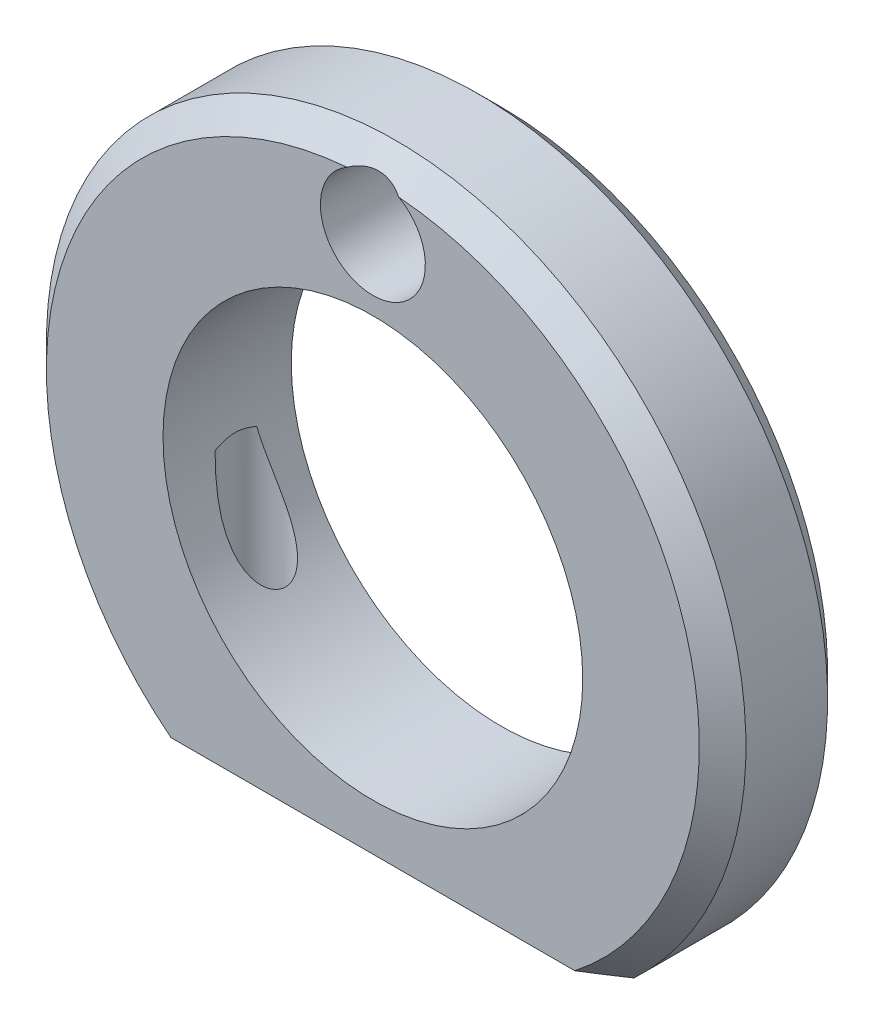
SolidWorks part; units mm, degrees
material "2A12"
ref_plane "前视基准面" through (0, 0, 0) normal (0, 0, 1) x (1, 0, 0)
ref_plane "上视基准面" through (0, 0, 0) normal (0, 1, 0) x (1, 0, 0)
ref_plane "右视基准面" through (0, 0, 0) normal (1, 0, 0) x (0, 0, -1)
sketch "草图1" plane through (0, 0, 0) normal (0, 0, 1) x (1, 0, 0)
  circle A0 centre (0, 0) radius 5.5
  circle A1 centre (0, 0) radius 7
  dimension "D1" = 11
  dimension "D2" = 14
extrude "拉伸1" add sketch "草图1" along normal mid plane 60
sketch "草图2" plane through (0, 0, 30) normal (0, 0, 1) x (1, 0, 0)
  line L0 (0, 0) -> (0, -11) construction
  line L1 (-10, 11) -> (10, 11) construction
  line L2 (-10, 11) -> (-10, -11) construction
  line L3 (-10, -11) -> (10, -11) construction
  line L4 (10, 11) -> (10, -11) construction
  circle A0 centre (0, 0) radius 5.5 construction
  circle A1 centre (0, 0) radius 5.5
  circle A2 centre (0, 0) radius 15
  dimension "D4" = 30
  dimension "D1" = 11
  dimension "D2" = 22
  dimension "D3" = 20
extrude "拉伸2" add sketch "草图2" against normal blind 7
mirror "镜向1" about plane through (0, 0, 0) normal (0, 0, 1) of "拉伸2"
sketch "草图4" plane through (0, 0, 30) normal (0, 0, 1) x (1, 0, 0)
  line L1 (-10.198, -11) -> (10.198, -11)
  line L2 (-10, -11) -> (10, -11) construction
  circle A0 centre (0, 0) radius 5.5 construction
  circle A1 centre (0, 0) radius 5.5
  circle A3 centre (0, 0) radius 15 construction
  arc A4 (10.198, -11) -> (-10.198, -11) centre (0, 0) ccw
extrude "拉伸3" [suppressed] add sketch "草图4" along normal blind 5
mirror "镜向2" [suppressed] about plane through (0, 0, 0) normal (0, 0, 1)
sketch "草图5" plane through (0, 0, 0) normal (1, 0, 0) x (0, 0, -1)
  line L0 (-30, 0) -> (30, 0) construction
  line L1 (-30, 15) -> (-30, -15) construction
  line L2 (30, -15) -> (30, 15) construction
  line L3 (-30, -11) -> (-24.5, -11)
  line L4 (-24.5, -11) -> (-24.5, -20)
  line L5 (24.5, -11) -> (24.5, -20)
  line L6 (-30, -11) -> (-30, -20)
  line L7 (-30, -20) -> (-24.5, -20)
  line L8 (30, -11) -> (30, -20)
  line L9 (30, -20) -> (24.5, -20)
  line L10 (24.5, -11) -> (30, -11)
  line L12 (-30, 15) -> (-30, -15) construction
  line L13 (30, -15) -> (30, 15) construction
  dimension "D1" = 9
  dimension "D2" = 11
  dimension "D4" = 5.5
  dimension "D5" = 5.5
extrude "拉伸4" cut sketch "草图5" against normal mid plane 30
sketch "草图6" plane through (0, -11, 0) normal (0, -1, 0) x (1, 0, 0)
  line L0 (0, 27.5) -> (0, -27.5) construction
  line L1 (-8, 27.5) -> (8, 27.5)
  line L2 (-8, 27.5) -> (-8, -27.5)
  line L3 (-8, -27.5) -> (8, -27.5)
  line L4 (8, 27.5) -> (8, -27.5)
  dimension "D1" = 16
  dimension "D2" = 55
hole_wizard "M3 螺纹孔1" positions "3D草图1" profile "草图7" tap size "M3" standard "GB"
sketch3d "3D草图1"
  point P0 (-8, -11, 27.5)
  point P3 (8, -11, 27.5)
  point P6 (-8, -11, -27.5)
  point P9 (8, -11, -27.5)
sketch "草图7" plane through (-8, -11, 27.5) normal (1, 0, 0) x (0, 0, -1)
  line L0 (0, 0) -> (0, 10.2511)
  line L1 (0, 10.2511) -> (1.25, 9.5)
  line L2 (1.25, 9.5) -> (1.25, 0)
  line L5 (1.25, 0) -> (0, 0)
  line L10 (0, 10.2511) -> (-1.25, 9.5) construction
  line L11 (0, -6.35) -> (0, 107.95) construction
  dimension "螺纹孔钻头直径" = 2.5
  dimension "螺纹孔钻头深度" = 9.5
  dimension "导头角度" = 118
cosmetic thread "孔螺蚊线1" parameters "D1"=8, "D2"=3
cosmetic thread "孔螺蚊线2" parameters "D1"=8, "D2"=3
cosmetic thread "孔螺蚊线3" parameters "D1"=8, "D2"=3
cosmetic thread "孔螺蚊线4" parameters "D1"=8, "D2"=3
chamfer "倒角1" [suppressed] distance 0.5 angle 45
chamfer "倒角2" [suppressed] distance 2 angle 45
chamfer "倒角3" [suppressed] distance 1 angle 45
fillet "圆角1" radius 1 2 edges at (-7, 0, -23) (7, 0, 23)
sketch "Sketch1" plane through (0, 0, 30) normal (0, 0, -1) x (-1, 0, 0)
  circle A0 centre (0, 0) radius 7.5
  dimension "D1" = 15
extrude "Extrude1" cut sketch "Sketch1" along normal blind 5
chamfer "Chamfer1" distance 1 angle 45 1 edges at (-5.5, 0, 25)
sketch "Sketch2" [suppressed] plane through (0, 0, -30) normal (0, 0, 1) x (1, 0, 0)
  line L0 (0, 0) -> (0, 11) construction
  line L1 (-12.5, 17) -> (12.5, 17)
  line L2 (-12.5, 17) -> (-12.5, 11)
  line L3 (-12.5, 11) -> (12.5, 11)
  line L4 (12.5, 17) -> (12.5, 11)
  dimension "D1" = 25
  dimension "D2" = 11
  dimension "D3" = 6
extrude "Extrude2" [suppressed] cut sketch "Sketch2" along normal up to surface (5.5 mm away)
sketch "Sketch4" [suppressed] plane through (0, 0, -24.5) normal (0, 0, -1) x (-1, 0, 0)
  circle A0 centre (0, 0) radius 17.5
  dimension "D1" = 35
extrude "Extrude4" [suppressed] cut sketch "Sketch4" against normal up to surface (54.5 mm away)
sketch "Sketch5" [suppressed] plane through (0, 0, -30) normal (0, 0, -1) x (-1, 0, 0)
  circle A0 centre (0, 0) radius 9
  dimension "D1" = 18
extrude "Extrude5" [suppressed] cut sketch "Sketch5" against normal blind 10
sketch "Sketch6" [suppressed] plane through (0, 0, -24.5) normal (0, 0, 1) x (1, 0, 0)
  circle A0 centre (0, 0) radius 15
extrude "Extrude6" [suppressed] cut sketch "Sketch6" against normal blind 0.5
chamfer "Chamfer3" [suppressed] distance 1 angle 45
sketch "草图8" [suppressed] plane through (0, 0, -30) normal (0, 0, -1) x (-1, 0, 0)
  line L3 (-10.198, -11) -> (10.198, -11)
  line L5 (-10.198, -11) -> (10.198, -11)
  circle A0 centre (0, 0) radius 9 construction
  circle A1 centre (0, 0) radius 9
  arc A2 (10.198, -11) -> (-10.198, -11) centre (0, 0) ccw
  arc A4 (10.198, -11) -> (-10.198, -11) centre (0, 0) ccw
  dimension "D1" = 0
extrude "拉伸5" [suppressed] add sketch "草图8" along normal blind 0.5
chamfer "倒角4" [suppressed] distance 1 angle 45
sketch "草图9" plane through (0, 0, -24.5) normal (0, 0, -1) x (-1, 0, 0)
  circle A0 centre (0, 0) radius 18
  dimension "D1" = 36
extrude "切除-拉伸1" cut sketch "草图9" against normal blind 55
sketch "草图10" plane through (0, 0, -30) normal (0, 0, -1) x (-1, 0, 0)
  circle A0 centre (0, 0) radius 9
  dimension "D1" = 18
extrude "切除-拉伸2" cut sketch "草图10" against normal through all
chamfer "倒角5" distance 1 angle 45 2 edges at (0, 15, -24.5) (0, 15, -30)
sketch "草图11" plane through (0, 0, -24.5) normal (0, 0, 1) x (1, 0, 0)
  circle A0 centre (0, 12) radius 2.25
  dimension "D1" = 4.5
  dimension "D2" = 12
extrude "切除-拉伸3" cut sketch "草图11" against normal blind 5.5
